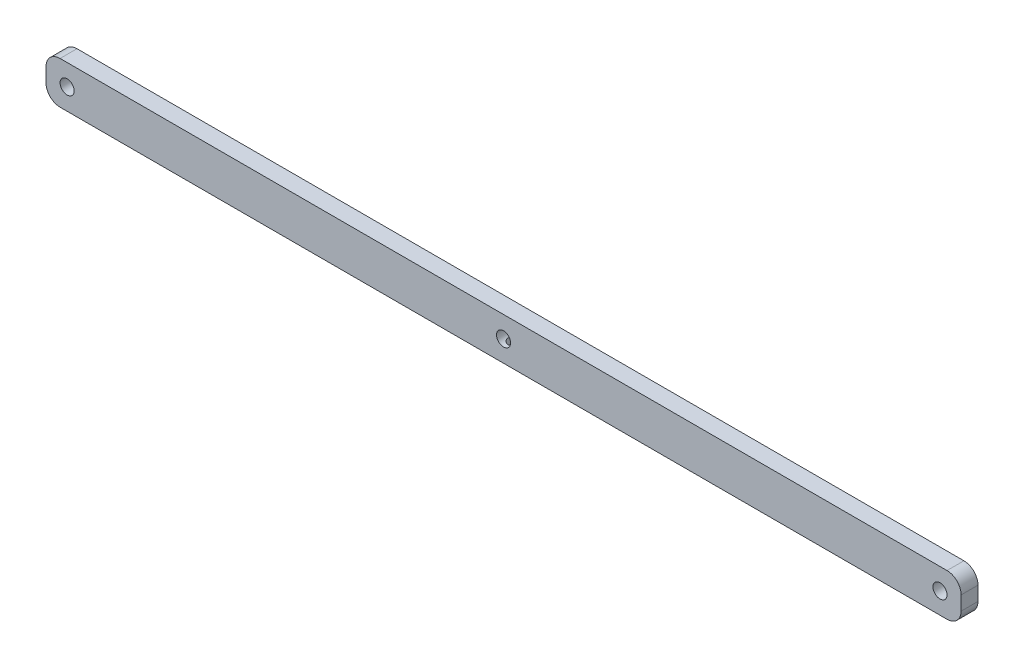
SolidWorks part; units mm, degrees
ref_plane "Płaszczyzna przednia" through (0, 0, 0) normal (0, 0, 1) x (1, 0, 0)
ref_plane "Płaszczyzna górna" through (0, 0, 0) normal (0, 1, 0) x (1, 0, 0)
ref_plane "Płaszczyzna prawa" through (0, 0, 0) normal (1, 0, 0) x (0, 0, -1)
sketch "Szkic1" plane through (0, 0, 0) normal (0, 0, 1) x (1, 0, 0)
  line L4 (162.5, 7.5) -> (162.5, -7.5)
  line L5 (162.5, -7.5) -> (-162.5, -7.5)
  line L6 (-162.5, -7.5) -> (-162.5, 7.5)
  line L7 (-162.5, 7.5) -> (162.5, 7.5)
  circle A4 centre (155, 0) radius 2.5
  circle A5 centre (-155, 0) radius 2.5
  circle A6 centre (0, 0) radius 2.5
  point P6 (162.5, 0)
  point P10 (0, 7.5)
  dimension "D1" = 5
  dimension "D3" = 5
  dimension "D7" = 5
  dimension "D5" = 15
  dimension "D6" = 325
  dimension "D2" = 310
  dimension "D4" = 155
extrude "Dodanie-wyciągnięcie1" add sketch "Szkic1" along normal mid plane 6
fillet "Zaokrąglenie1" radius 5 4 edges at (-162.5, -7.5, 0) (-162.5, 7.5, 0) (162.5, 7.5, 0) (162.5, -7.5, 0)
hole_wizard "Otwory ustalające Ø3.0mm1" positions "Szkic2" profile "Szkic3" hole size "Ø3.0" standard "Ansi Metric"
sketch "Szkic2" plane through (0, -7.5, 0) normal (0, -1, 0) x (-1, 0, 0)
  point P0 (0, 0)
sketch "Szkic3" plane through (0, -7.5, 0) normal (1, 0, 0) x (0, 0, -1)
  line L0 (0, 0) -> (0, 8.4003)
  line L1 (0, 8.4003) -> (1.5, 7.499)
  line L2 (1.5, 7.499) -> (1.5, 0)
  line L5 (1.5, 0) -> (0, 0)
  line L10 (0, 8.4003) -> (-1.5, 7.499) construction
  line L11 (0, -6.35) -> (0, 107.95) construction
  dimension "Średnica otworu" = 3
  dimension "Głębokość otworu" = 7.499
  dimension "Kąt wiertła" = 118
equation "\"D4@Szkic1\"=\"D2@Szkic1\"/2"
